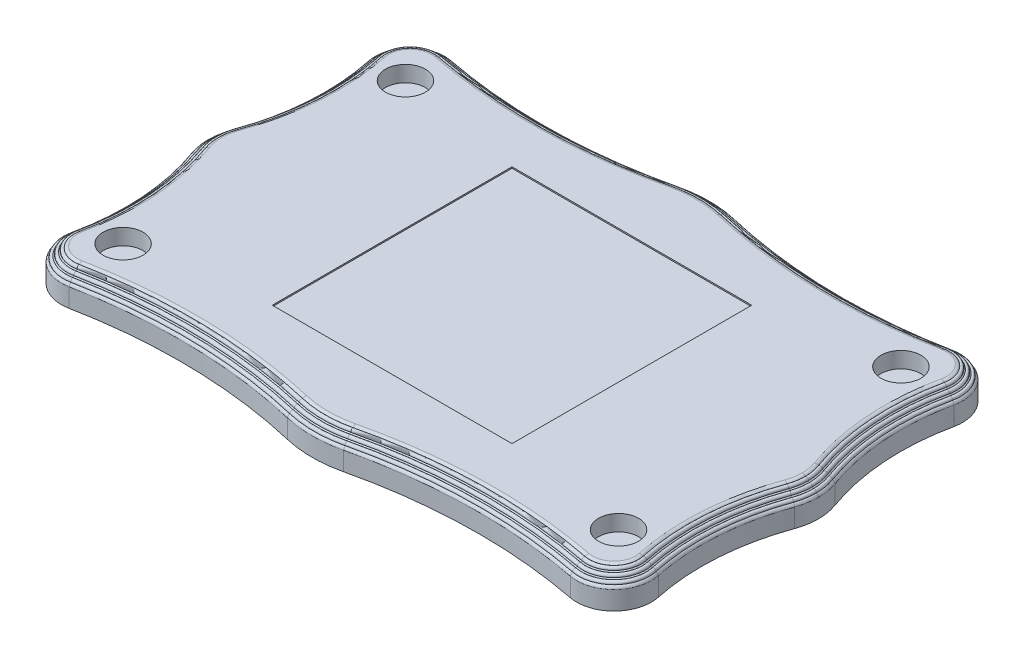
SolidWorks part; units mm, degrees
ref_plane "Front Plane" through (0, 0, 0) normal (0, 0, 1) x (1, 0, 0)
ref_plane "Top Plane" through (0, 0, 0) normal (0, 1, 0) x (1, 0, 0)
ref_plane "Right Plane" through (0, 0, 0) normal (1, 0, 0) x (0, 0, -1)
sketch "Sketch1" plane through (0, 0, 0) normal (0, 1, 0) x (1, 0, 0)
  line L0 (0, 22.5) -> (0, 30.5) construction
  line L1 (50.5, -30.5) -> (-50.5, -30.5) construction
  line L2 (50.5, -30.5) -> (50.5, 30.5) construction
  line L3 (50.5, 30.5) -> (-50.5, 30.5) construction
  line L4 (-50.5, -30.5) -> (-50.5, 30.5) construction
  line L5 (50.5, -30.5) -> (-50.5, 30.5) construction
  line L6 (50.5, 30.5) -> (-50.5, -30.5) construction
  line L7 (-42.5, 22.5) -> (42.5, 22.5) construction
  line L8 (-42.5, 22.5) -> (-42.5, -22.5) construction
  line L9 (-42.5, -22.5) -> (42.5, -22.5) construction
  line L10 (42.5, 22.5) -> (42.5, -22.5) construction
  line L11 (-42.5, 22.5) -> (42.5, -22.5) construction
  line L12 (-42.5, -22.5) -> (42.5, 22.5) construction
  line L13 (42.5, 0) -> (50.5, 0) construction
  line L14 (57.5, 0) -> (50.5, 0) construction
  line L19 (-46.5, 26.5) -> (46.5, 26.5) construction
  line L20 (-46.5, 26.5) -> (-46.5, -26.5) construction
  line L21 (-46.5, -26.5) -> (46.5, -26.5) construction
  line L22 (46.5, 26.5) -> (46.5, -26.5) construction
  line L23 (-46.5, 26.5) -> (46.5, -26.5) construction
  line L24 (-46.5, -26.5) -> (46.5, 26.5) construction
  line L25 (-57.5, 37.5) -> (57.5, 37.5)
  line L26 (-57.5, 37.5) -> (-57.5, -37.5)
  line L27 (-57.5, -37.5) -> (57.5, -37.5)
  line L28 (57.5, 37.5) -> (57.5, -37.5)
  line L29 (-57.5, 37.5) -> (57.5, -37.5) construction
  line L30 (-57.5, -37.5) -> (57.5, 37.5) construction
  line L31 (0, 30.5) -> (0, 37.5) construction
  circle A0 centre (46.5, 26.5) radius 3.75 construction
  circle A1 centre (-46.5, 26.5) radius 3.75 construction
  circle A2 centre (46.5, -26.5) radius 3.75 construction
  circle A3 centre (-46.5, -26.5) radius 3.75 construction
  point P0 (0, 0)
  point P6 (0, 0)
  point P17 (0, 0)
  point P24 (0, 0)
  point P29 (46.5, 0)
  point P30 (0, 26.5)
  dimension "D5" = 7.5
  dimension "D1" = 85
  dimension "D2" = 45
  dimension "D3" = 8
  dimension "D4" = 7
extrude "Base" add sketch "Sketch1" along normal blind 6
sketch "Path" plane through (0, 6, 0) normal (0, 1, 0) x (1, 0, 0)
  line L0 (51.25, 0) -> (50.5, 0) construction
  line L1 (28.0361, 31.25) -> (28.0361, 30.5) construction
  line L2 (-4.5909, 34.5) -> (4.5909, 34.5) construction
  line L3 (-54.5, 4.5909) -> (-54.5, -4.5909) construction
  line L4 (-50.5, -30.5) -> (-50.5, 30.5) construction
  line L5 (-50.5, 30.5) -> (50.5, 30.5) construction
  line L6 (-57.5, 37.5) -> (-57.5, -37.5) construction
  line L7 (57.5, 37.5) -> (-57.5, 37.5) construction
  line L8 (0, 34.5) -> (0, 37.5) construction
  line L9 (-54.5, 0) -> (-57.5, 0) construction
  line L10 (0, 0) -> (-50.5, 30.5) construction
  line L11 (-51.25, 31.25) -> (-51.25, -31.25) construction
  line L12 (-51.25, 31.25) -> (51.25, 31.25) construction
  line L13 (-50.5, 0) -> (-41.3182, 0) construction
  line L14 (-41.3182, 0) -> (-32.1364, 0) construction
  line L15 (-32.1364, 0) -> (-22.9545, 0) construction
  line L16 (-22.9545, 0) -> (-13.7727, 0) construction
  line L17 (-13.7727, 0) -> (-4.5909, 0) construction
  line L18 (-4.5909, 0) -> (4.5909, 0) construction
  line L19 (-4.5909, 33.9678) -> (4.5909, 33.9678) construction
  line L20 (-28.0361, 30.5) -> (-28.0361, 24.9545) construction
  line L21 (-28.0361, 24.9545) -> (-28.0361, 19.4091) construction
  line L22 (-28.0361, 19.4091) -> (-28.0361, 13.8636) construction
  line L23 (-28.0361, 13.8636) -> (-28.0361, 8.3182) construction
  line L24 (-28.0361, 8.3182) -> (-28.0361, 2.7727) construction
  line L25 (-28.0361, 2.7727) -> (-28.0361, -2.7727) construction
  line L26 (-54.0165, 2.7727) -> (-54.0165, -2.7727) construction
  line L27 (0, 37.5) -> (0, 46.6818) construction
  line L28 (-57.5, 0) -> (-66.6818, 0) construction
  line L29 (-28.0361, 31.25) -> (-28.0361, 30.5) construction
  line L30 (-51.25, 0) -> (-50.5, 0) construction
  line L31 (54.0165, 2.7727) -> (54.0165, -2.7727) construction
  line L32 (28.0361, 2.7727) -> (28.0361, -2.7727) construction
  line L33 (28.0361, 8.3182) -> (28.0361, 2.7727) construction
  line L34 (28.0361, 13.8636) -> (28.0361, 8.3182) construction
  line L35 (28.0361, 19.4091) -> (28.0361, 13.8636) construction
  line L36 (28.0361, 24.9545) -> (28.0361, 19.4091) construction
  line L37 (28.0361, 30.5) -> (28.0361, 24.9545) construction
  line L38 (13.7727, 0) -> (4.5909, 0) construction
  line L39 (22.9545, 0) -> (13.7727, 0) construction
  line L40 (32.1364, 0) -> (22.9545, 0) construction
  line L41 (41.3182, 0) -> (32.1364, 0) construction
  line L42 (50.5, 0) -> (41.3182, 0) construction
  line L43 (51.25, 31.25) -> (51.25, -31.25) construction
  line L44 (0, 0) -> (50.5, 30.5) construction
  line L45 (54.5, 0) -> (57.5, 0) construction
  line L46 (50.5, -30.5) -> (50.5, 30.5) construction
  line L47 (54.5, 4.5909) -> (54.5, -4.5909) construction
  line L48 (0, 0) -> (50.5, -30.5) construction
  line L49 (50.5, 0) -> (41.3182, 0) construction
  line L50 (41.3182, 0) -> (32.1364, 0) construction
  line L51 (32.1364, 0) -> (22.9545, 0) construction
  line L52 (22.9545, 0) -> (13.7727, 0) construction
  line L53 (13.7727, 0) -> (4.5909, 0) construction
  line L54 (28.0361, -30.5) -> (28.0361, -24.9545) construction
  line L55 (28.0361, -24.9545) -> (28.0361, -19.4091) construction
  line L56 (28.0361, -19.4091) -> (28.0361, -13.8636) construction
  line L57 (28.0361, -13.8636) -> (28.0361, -8.3182) construction
  line L58 (28.0361, -8.3182) -> (28.0361, -2.7727) construction
  line L59 (-51.25, 0) -> (-50.5, 0) construction
  line L60 (-28.0361, -31.25) -> (-28.0361, -30.5) construction
  line L61 (0, -37.5) -> (0, -46.6818) construction
  line L62 (-28.0361, -8.3182) -> (-28.0361, -2.7727) construction
  line L63 (-28.0361, -13.8636) -> (-28.0361, -8.3182) construction
  line L64 (-28.0361, -19.4091) -> (-28.0361, -13.8636) construction
  line L65 (-28.0361, -24.9545) -> (-28.0361, -19.4091) construction
  line L66 (-28.0361, -30.5) -> (-28.0361, -24.9545) construction
  line L67 (-4.5909, -33.9678) -> (4.5909, -33.9678) construction
  line L68 (-4.5909, 0) -> (4.5909, 0) construction
  line L69 (-13.7727, 0) -> (-4.5909, 0) construction
  line L70 (-22.9545, 0) -> (-13.7727, 0) construction
  line L71 (-32.1364, 0) -> (-22.9545, 0) construction
  line L72 (-41.3182, 0) -> (-32.1364, 0) construction
  line L73 (-50.5, 0) -> (-41.3182, 0) construction
  line L74 (-51.25, -31.25) -> (51.25, -31.25) construction
  line L75 (0, 0) -> (-50.5, -30.5) construction
  line L76 (0, -34.5) -> (0, -37.5) construction
  line L77 (-50.5, -30.5) -> (50.5, -30.5) construction
  line L78 (-4.5909, -34.5) -> (4.5909, -34.5) construction
  line L79 (28.0361, -31.25) -> (28.0361, -30.5) construction
  line L80 (51.25, 0) -> (50.5, 0) construction
  arc A0 (4.5909, 33.9678) -> (-4.5909, 33.9678) centre (0, 14.4322) ccw
  arc A1 (-54.0165, -2.7727) -> (-54.0165, 2.7727) centre (-46.3077, 0) cw
  circle A2 centre (-48.36, 29.2075) radius 4 construction
  arc A3 (-54.0165, 2.7727) -> (-52.2727, 28.3765) centre (-98.1256, 18.6381) ccw
  arc A4 (-4.5909, 33.9678) -> (-47.5966, 33.134) centre (-28.0361, 133.734) cw
  arc A5 (-52.2727, 28.3765) -> (-47.5966, 33.134) centre (-48.36, 29.2075) cw
  circle A6 centre (48.36, 29.2075) radius 4 construction
  arc A7 (52.2727, 28.3765) -> (47.5966, 33.134) centre (48.36, 29.2075) ccw
  arc A8 (4.5909, 33.9678) -> (47.5966, 33.134) centre (28.0361, 133.734) ccw
  arc A9 (54.0165, 2.7727) -> (52.2727, 28.3765) centre (98.1256, 18.6381) cw
  arc A10 (54.0165, -2.7727) -> (54.0165, 2.7727) centre (46.3077, 0) ccw
  circle A11 centre (48.36, -29.2075) radius 4 construction
  circle A12 centre (-48.36, -29.2075) radius 4 construction
  arc A13 (54.0165, -2.7727) -> (52.2727, -28.3765) centre (98.1256, -18.6381) ccw
  arc A14 (4.5909, -33.9678) -> (47.5966, -33.134) centre (28.0361, -133.734) cw
  arc A15 (52.2727, -28.3765) -> (47.5966, -33.134) centre (48.36, -29.2075) cw
  arc A16 (-52.2727, -28.3765) -> (-47.5966, -33.134) centre (-48.36, -29.2075) ccw
  arc A17 (-4.5909, -33.9678) -> (-47.5966, -33.134) centre (-28.0361, -133.734) ccw
  arc A18 (-54.0165, -2.7727) -> (-52.2727, -28.3765) centre (-98.1256, -18.6381) cw
  arc A19 (4.5909, -33.9678) -> (-4.5909, -33.9678) centre (0, -14.4322) cw
  point P37 (-50.5, 0)
  point P72 (0, 33.9678)
  point P73 (0, 0)
  point P78 (0, 31.25)
  point P82 (0, 30.5)
  point P96 (50.5, 0)
  point P97 (51.25, 0)
  point P109 (28.0361, 0)
  point P110 (54.0165, 0)
  point P117 (-54.0165, 0)
  point P118 (-28.0361, 0)
  point P130 (-51.25, 0)
  point P132 (-50.5, 0)
  point P146 (0, -30.5)
  point P147 (0, -31.25)
  point P148 (0, 0)
  point P149 (0, -33.9678)
  dimension "D5" = 8
  dimension "D1" = 7
  dimension "D2" = 7
  dimension "D3" = 3
  dimension "D4" = 2.5
  dimension "D7" = 0.75
sketch "Profile" plane through (0, 0, 0) normal (0, 0, 1) x (1, 0, 0)
  line L0 (54.5, 6) -> (57.5, 6)
  line L1 (57.5, 6) -> (57.5, 3.5) construction
  line L2 (57.5, 6) -> (55.25, 5.375) construction
  line L3 (57.5, 6) -> (56, 4.75) construction
  line L4 (57.5, 6) -> (56.75, 4.125) construction
  line L5 (55.25, 5.375) -> (54.5, 6) construction
  line L6 (55.25, 5.375) -> (56, 4.75) construction
  line L7 (56, 4.75) -> (56.75, 4.125) construction
  line L8 (56.75, 4.125) -> (57.5, 3.5) construction
  line L9 (56, 4.75) -> (57.5, 4.75) construction
  line L10 (56.75, 4.125) -> (57.5, 4.125) construction
  line L11 (55.25, 5.375) -> (57.5, 5.375) construction
  line L12 (57.5, 6) -> (67.5, 8)
  line L13 (67.5, 8) -> (67.5, 3.5)
  line L15 (57.5, 3.5) -> (57.5, -4.5)
  line L16 (57.5, -4.5) -> (67.5, -4.5)
  line L17 (57.5, 3.5) -> (67.5, 3.5) construction
  line L18 (67.5, -4.5) -> (67.5, 3.5)
  circle A0 centre (55.25, 5.375) radius 0.39 construction
  circle A1 centre (56, 4.75) radius 0.39 construction
  circle A2 centre (56.75, 4.125) radius 0.39 construction
  arc A3 (56.75, 4.125) -> (57.5, 3.5) centre (56.75, 3.3625) cw construction
  arc A4 (56, 4.75) -> (56.75, 4.125) centre (56, 3.9875) cw construction
  arc A5 (55.25, 5.375) -> (56, 4.75) centre (55.25, 4.6125) cw construction
  arc A6 (54.5, 6) -> (55.25, 5.375) centre (54.5, 5.2375) cw construction
  arc A7 (54.5, 6) -> (55.0839, 5.7279) centre (54.5, 5.2375) cw
  arc A8 (55.0839, 5.7279) -> (55.627, 5.2753) centre (55.25, 5.375) cw
  arc A9 (55.627, 5.2753) -> (55.8339, 5.1029) centre (55.25, 4.6125) cw
  arc A10 (55.8339, 5.1029) -> (56.377, 4.6503) centre (56, 4.75) cw
  arc A11 (56.377, 4.6503) -> (56.5839, 4.4779) centre (56, 3.9875) cw
  arc A12 (56.5839, 4.4779) -> (57.127, 4.0253) centre (56.75, 4.125) cw
  arc A13 (57.127, 4.0253) -> (57.5, 3.5) centre (56.75, 3.3625) cw
  dimension "D3" = 0.78
  dimension "D1" = 3
  dimension "D2" = 2.5
  dimension "D4" = 10
  dimension "D5" = 8
sweep "Sweep Cut" cut profiles "Profile" path "Path"
sketch "Sketch5" plane through (0, 6, 0) normal (0, 1, 0) x (1, 0, 0)
  line L1 (22.5, -22.5) -> (-22.5, -22.5)
  line L2 (22.5, -22.5) -> (22.5, 22.5)
  line L3 (22.5, 22.5) -> (-22.5, 22.5)
  line L4 (-22.5, -22.5) -> (-22.5, 22.5)
  line L5 (22.5, -22.5) -> (-22.5, 22.5) construction
  line L6 (22.5, 22.5) -> (-22.5, -22.5) construction
  point P0 (0, 0)
  dimension "D1" = 45
extrude "Pyramid Base Cut" cut sketch "Sketch5" against normal blind 0.25
sketch "Sketch4" plane through (0, 6, 0) normal (0, 1, 0) x (1, 0, 0)
  circle A0 centre (-46.5, -26.5) radius 3.75 construction
  circle A1 centre (46.5, -26.5) radius 3.75 construction
  circle A2 centre (46.5, 26.5) radius 3.75 construction
  circle A3 centre (-46.5, 26.5) radius 3.75 construction
  circle A4 centre (-46.5, -26.5) radius 3.75
  circle A5 centre (46.5, -26.5) radius 3.75
  circle A6 centre (46.5, 26.5) radius 3.75
  circle A7 centre (-46.5, 26.5) radius 3.75
extrude "Post Hole Cut" cut sketch "Sketch4" against normal blind 3
equation "\"D1@Sketch1\"=\"screen height\""
equation "\"D2@Sketch1\"=\"screen width\""
equation "\"D5@Sketch1\"=\"support pole loose fit hole dia\""
equation "\"D1@Sketch5\"=\"screen width\""
equation "\"screen width\"= 45.00mm"
equation "\"screen height\"= 85.00mm"
equation "\"top cutoff\" = 2.00mm"
equation "\"A\" = \"screen width\" / 2"
equation "\"B\" = \"screen width\" / 2"
equation "\"screen hypotenuse\" = sqr ( ( \"A\" * \"A\" ) + ( \"B\" * \"B\" ) )"
equation "\"a2\" = \"top cutoff\" "
equation "\"b2\" = \"top cutoff\""
equation "\"top cutoff hypotenuse\" = sqr ( ( \"a2\" * \"a2\" ) + ( \"b2\" * \"b2\" ) )"
equation "\"total hypotenuse\" = \"screen hypotenuse\" - \"top cutoff hypotenuse\""
equation "\"image display width\" = ( \"A\" / 3 ) * 2"
equation "\"image display height\" = ( \"B\" / 3 ) * 2"
equation "\"support pole dia\" = 7.00mm"
equation "\"support pole loose fit hole dia\" = \"support pole dia\"+0.5"
equation "\"support pole tight fit hole dia\" = \"support pole dia\"+0.25"
